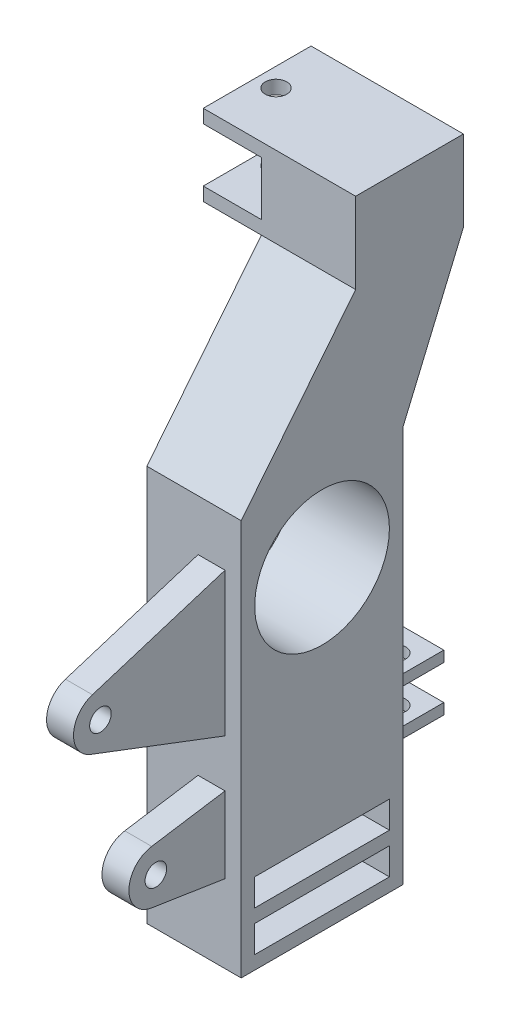
SolidWorks part; units mm, degrees
ref_plane "Front Plane" through (0, 0, 0) normal (0, 0, 1) x (1, 0, 0)
ref_plane "Top Plane" through (0, 0, 0) normal (0, 1, 0) x (1, 0, 0)
ref_plane "Right Plane" through (0, 0, 0) normal (1, 0, 0) x (0, 0, -1)
sketch3d "3DSketch1"
  line L0 (0, 0, 0) -> (0, 205, 0) construction
  line L1 (0, 205, 0) -> (0, 205, -32.4688) construction
  line L3 (0, 205, -32.4688) -> (-21.5464, 205, -32.4688) construction
  line L4 (-21.5464, 205, -32.4688) -> (0, 0, 0) construction
sketch "Sketch1" plane through (0, 0, 0) normal (1, 0, 0) x (0, 0, -1)
  line L0 (0, 0) -> (-25, 0) construction
  line L2 (-25, 5) -> (25, 5)
  line L4 (25, -5) -> (-25, -5)
  line L8 (30, -10) -> (-30, -10)
  line L10 (30, -10) -> (30, 10)
  line L11 (0, 10) -> (-25, 10)
  line L12 (-30, -10) -> (-30, 10)
  line L13 (30, 10) -> (30, 106.969)
  line L14 (-25, 5) -> (-25, -5)
  line L15 (-30, 106.969) -> (-30, 10)
  line L16 (30, 106.969) -> (30, 136.969)
  line L17 (-30, 106.969) -> (-30, 136.969)
  line L18 (-30, 136.969) -> (30, 136.969)
  line L19 (32.4688, 205) -> (52.4688, 205) construction
  line L20 (32.4688, 205) -> (12.4688, 205) construction
  line L21 (0, 0) -> (0, 205) construction
  line L22 (52.4688, 205) -> (52.4688, 190)
  line L23 (52.4688, 205) -> (52.4688, 220)
  line L24 (52.4688, 220) -> (12.4688, 220)
  line L25 (12.4688, 220) -> (12.4688, 190)
  line L26 (12.4688, 190) -> (52.4688, 190)
  line L27 (52.4688, 190) -> (30, 136.969)
  line L28 (12.4688, 190) -> (-30, 136.969)
  line L29 (25, 5) -> (25, -5)
  line L30 (0, 10) -> (25, 10)
  line L31 (25, 10) -> (25, 20)
  line L32 (25, 20) -> (-25, 20)
  line L33 (-25, 20) -> (-25, 10)
  circle A0 centre (0, 106.969) radius 25
  dimension "D2" = 30
  dimension "D1" = 30
  dimension "D3" = 25
  dimension "D4" = 25
extrude "Boss-Extrude1" add sketch "Sketch1" along normal blind 28 and the other way blind 7 contours L25 L26 L22 L23 L24 | L26 L28 L18 L27 | L18 L17 L15 L12 L8 L10 L13 L16 A0 L33 L32 L31 L30 L11 L2 L29 L4 L14
sketch "Sketch3" plane through (0, 0, -52.4688) normal (0, 0, -1) x (-1, 0, 0)
  line L0 (7, 190) -> (28.5464, 190)
  line L1 (28.5464, 190) -> (28.5464, 195)
  line L2 (28.5464, 195) -> (7, 195)
  line L4 (7, 220) -> (28.5464, 220)
  line L5 (28.5464, 220) -> (28.5464, 215)
  line L6 (28.5464, 215) -> (7, 215)
  line L8 (7, 220) -> (7, 215)
  line L9 (7, 195) -> (7, 190)
  line L10 (7, 220) -> (7, 190) construction
  dimension "D1" = 7
extrude "Boss-Extrude2" add sketch "Sketch3" against normal blind 40
sketch "Sketch4" plane through (0, 220, 0) normal (0, 1, 0) x (1, 0, 0)
  circle A0 centre (-21.5464, 32.4688) radius 4
extrude "Cut-Extrude1" cut sketch "Sketch4" against normal blind 40 and the other way through all
sketch "Sketch5" plane through (0, -10, 0) normal (0, -1, 0) x (1, 0, 0)
  circle A0 centre (0, 0) radius 4
  dimension "D1" = 8
extrude "Cut-Extrude2" cut sketch "Sketch5" against normal blind 25 contours A0
sketch "Sketch6" plane through (0, 0, -30) normal (0, 0, -1) x (-1, 0, 0)
  line L0 (7, 37.9744) -> (-8.1921, 37.9744)
  line L1 (7, -10) -> (7, 136.969) construction
  line L3 (-8.1921, 17.1215) -> (7, 17.1215)
  line L5 (-8.1921, 33.9744) -> (7, 33.9744)
  line L7 (7, 21.1215) -> (-8.1921, 21.1215)
  line L8 (-8.1921, 37.9744) -> (-8.1921, 33.9744)
  line L9 (-8.1921, 21.1215) -> (-8.1921, 17.1215)
  line L10 (7, 37.9744) -> (7, 33.9744)
  line L11 (7, 21.1215) -> (7, 17.1215)
extrude "Boss-Extrude4" add sketch "Sketch6" along normal blind 35
sketch "Sketch7" plane through (0, 17.1215, 0) normal (0, -1, 0) x (1, 0, 0)
  line L0 (8.1921, -65) -> (-7, -65) construction
  circle A0 centre (0, -55) radius 4
  dimension "D1" = 10
extrude "Cut-Extrude3" cut sketch "Sketch7" against normal blind 35
ref_plane "Plane1" through (17, 0, 0) normal (1, 0, 0) x (0, 0, -1)
sketch "Sketch8" plane through (17, 0, 0) normal (1, 0, 0) x (0, 0, -1)
  line L0 (-30, 118.0603) -> (-30, 64.8028)
  line L1 (-30, -10) -> (-30, 136.969) construction
  line L2 (-30, 118.0603) -> (-79.2158, 102.6383)
  line L3 (-79.7826, 83.7498) -> (-30, 64.8028)
  line L4 (-30, 47.1255) -> (-30, 18.906)
  line L5 (-30, 18.906) -> (-57.2033, 23.1344)
  line L6 (-57.2033, 42.8971) -> (-30, 47.1255)
  arc A0 (-79.7826, 83.7498) -> (-79.2158, 102.6383) centre (-76.2256, 93.0958) cw
  circle A1 centre (-76.2256, 93.0958) radius 4
  arc A2 (-57.2033, 42.8971) -> (-57.2033, 23.1344) centre (-55.6674, 33.0157) ccw
  circle A3 centre (-55.6674, 33.0157) radius 4
  dimension "D1" = 10
  dimension "D2" = 10
  dimension "D3" = 63.5
extrude "Boss-Extrude5" add sketch "Sketch8" along normal blind 5 and the other way blind 5
